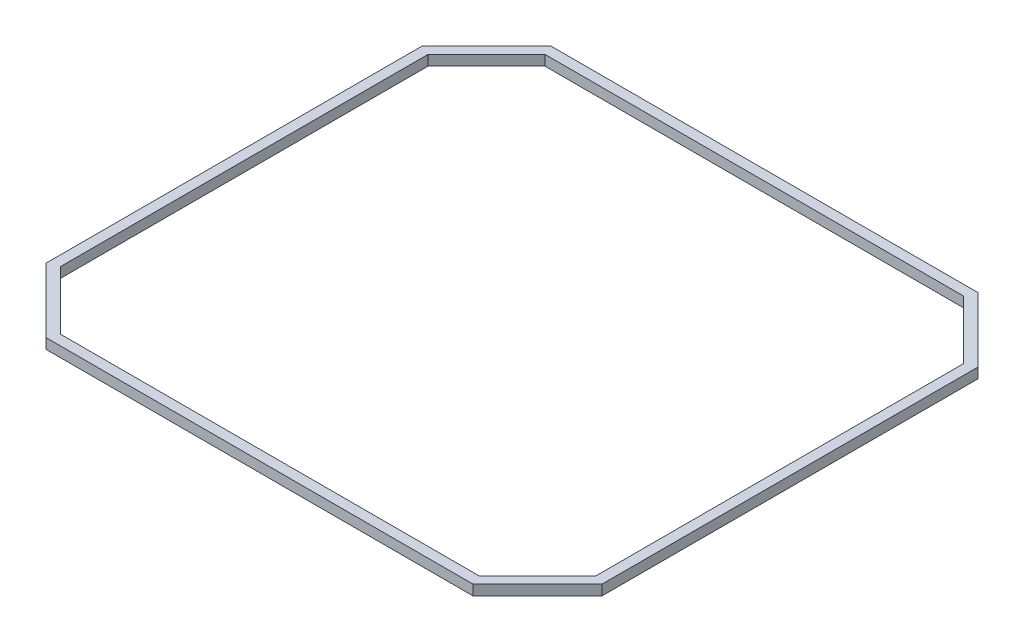
SolidWorks part; units mm, degrees
material "Silicon Rubber"
ref_plane "Front Plane" through (0, 0, 0) normal (0, 0, 1) x (1, 0, 0)
ref_plane "Top Plane" through (0, 0, 0) normal (0, 1, 0) x (1, 0, 0)
ref_plane "Right Plane" through (0, 0, 0) normal (1, 0, 0) x (0, 0, -1)
sketch "Seal Sketch" plane through (0, 0, 0) normal (0, 1, 0) x (1, 0, 0)
  line L0 (-41.864, 49.5) -> (-54.5, 36.864)
  line L1 (-54.5, 36.864) -> (-54.5, -36.864)
  line L2 (-54.5, -36.864) -> (-41.864, -49.5)
  line L3 (-41.864, -49.5) -> (41.864, -49.5)
  line L4 (41.864, -49.5) -> (54.5, -36.864)
  line L5 (54.5, -36.864) -> (54.5, 36.864)
  line L6 (54.5, 36.864) -> (41.864, 49.5)
  line L7 (41.864, 49.5) -> (-41.864, 49.5)
  line L8 (-41.0355, 47.5) -> (-52.5, 36.0355)
  line L9 (-52.5, 36.0355) -> (-52.5, -36.0355)
  line L10 (-52.5, -36.0355) -> (-41.0355, -47.5)
  line L11 (-41.0355, -47.5) -> (41.0355, -47.5)
  line L12 (41.0355, -47.5) -> (52.5, -36.0355)
  line L13 (52.5, -36.0355) -> (52.5, 36.0355)
  line L14 (52.5, 36.0355) -> (41.0355, 47.5)
  line L15 (41.0355, 47.5) -> (-41.0355, 47.5)
extrude "Seal" add sketch "Seal Sketch" along normal blind 2
